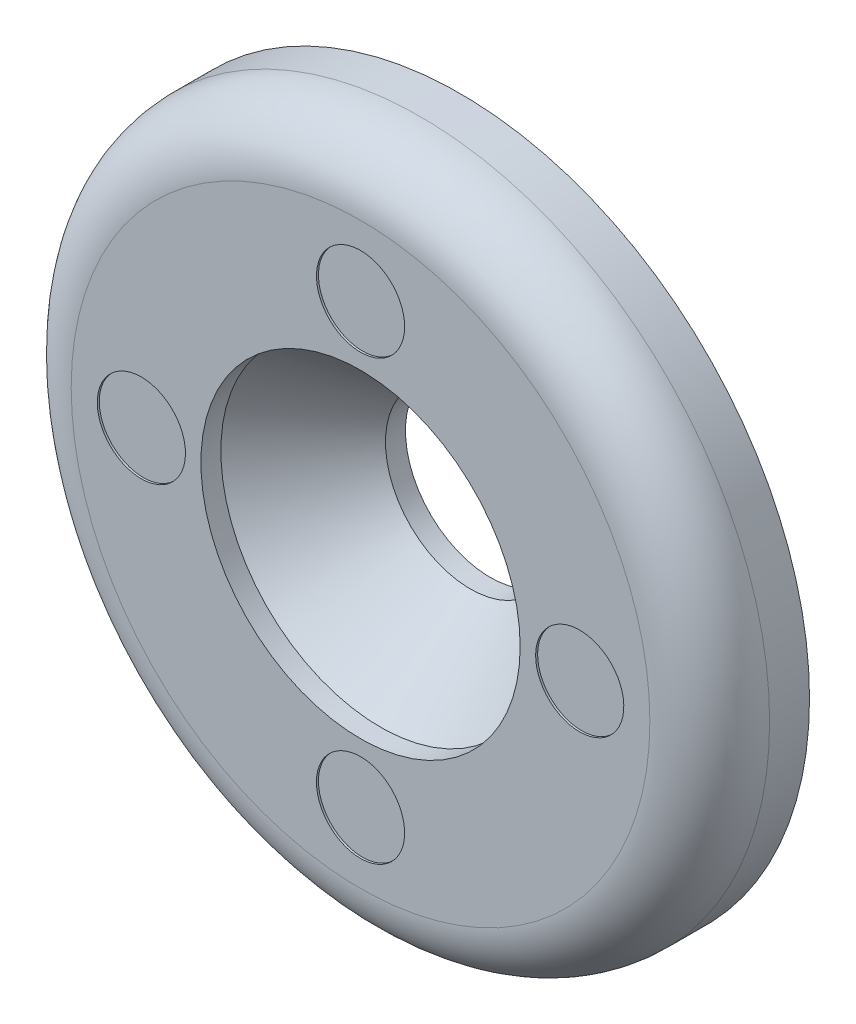
SolidWorks part; units mm, degrees
material "Alumina"
ref_plane "Plano frontal" through (0, 0, 0) normal (0, 0, 1) x (1, 0, 0)
ref_plane "Plano superior" through (0, 0, 0) normal (0, 1, 0) x (1, 0, 0)
ref_plane "Plano direito" through (0, 0, 0) normal (1, 0, 0) x (0, 0, -1)
sketch "Esboço1" plane through (0, 0, 0) normal (1, 0, 0) x (0, 0, -1)
  line L1 (6.5, 4.25) -> (6.5, 8.25)
  line L2 (6.5, 8.25) -> (5, 9.5)
  line L3 (5, 9.5) -> (5, 17.5)
  line L4 (5, 17.5) -> (0, 17.5)
  line L5 (0, 17.5) -> (0, 8)
  line L6 (0, 8) -> (1, 8)
  line L7 (1, 8) -> (5.5, 4.25)
  line L8 (5.5, 4.25) -> (6.5, 4.25)
  line L9 (0, 0) -> (6.5, 0) construction
  dimension "D1" = 5
  dimension "D2" = 8
  dimension "D3" = 1
  dimension "D4" = 6.5
  dimension "D5" = 4.25
  dimension "D6" = 17.5
  dimension "D7" = 1
  dimension "D8" = 4
  dimension "D9" = 8
revolve "Revolução1" add sketch "Esboço1" angle 360 about L9
fillet "Filete1" radius 3 1 edges at (17.5, 0, 0)
sketch "Esboço2" plane through (0, 0, 0) normal (0, 0, 1) x (1, 0, 0)
  circle A0 centre (0, 10.9833) radius 2.2091
extrude "Corte-extrusão1" cut sketch "Esboço2" against normal blind 0.1
pattern_circular "PadrãoCircular1" count 4 over 360 about axis through (0, 0, 0) along (0, 0, 1) of "Corte-extrusão1"
fillet "Filete2" radius 1 2 edges at (9.5, 0, -5) (8.25, 0, -6.5)
